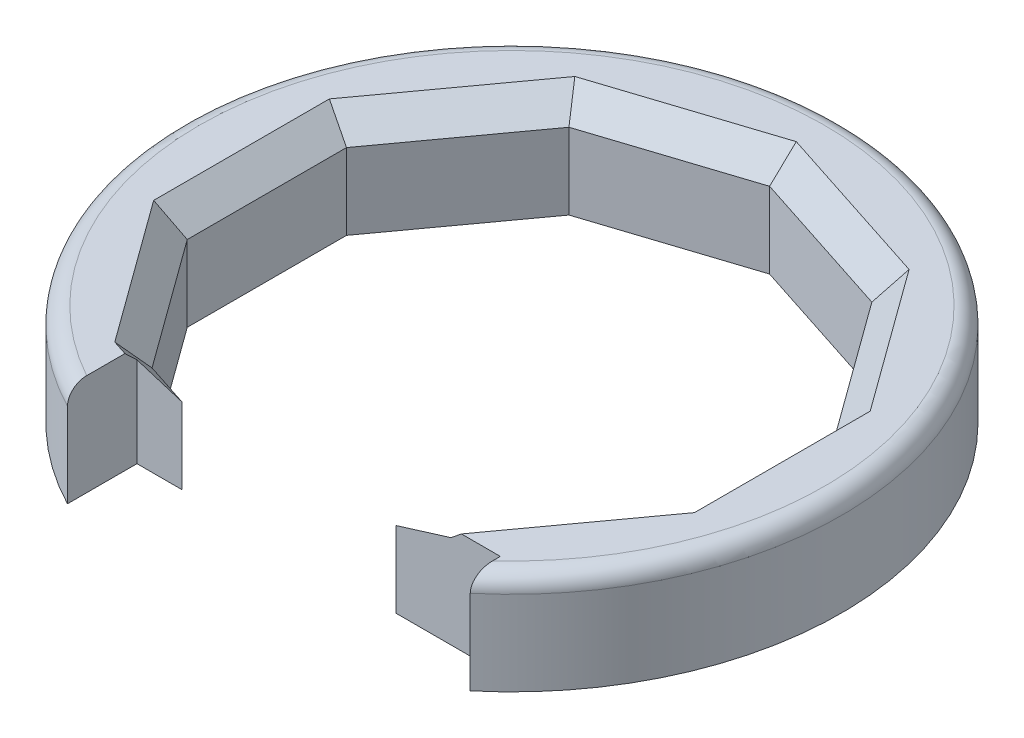
SolidWorks part; units mm, degrees
ref_plane "Front Plane" through (0, 0, 0) normal (0, 0, 1) x (1, 0, 0)
ref_plane "Top Plane" through (0, 0, 0) normal (0, 1, 0) x (1, 0, 0)
ref_plane "Right Plane" through (0, 0, 0) normal (1, 0, 0) x (0, 0, -1)
sketch "Sketch1" plane through (0, 0, 0) normal (0, 1, 0) x (1, 0, 0)
  line L1 (17.923, 24.6689) -> (0, 30.4924)
  line L2 (0, 30.4924) -> (-17.923, 24.6689)
  line L3 (-17.923, 24.6689) -> (-29, 9.4227)
  line L4 (-29, 9.4227) -> (-29, -9.4227)
  line L5 (-29, -9.4227) -> (-17.923, -24.6689)
  line L6 (-17.923, -24.6689) -> (0, -30.4924)
  line L7 (0, -30.4924) -> (17.923, -24.6689)
  line L8 (17.923, -24.6689) -> (29, -9.4227)
  line L9 (29, -9.4227) -> (29, 9.4227)
  line L10 (29, 9.4227) -> (17.923, 24.6689)
  circle A0 centre (0, 0) radius 39
  circle A1 centre (0, 0) radius 29 construction
  dimension "D1" = 78
  dimension "D2" = 10
extrude "Boss-Extrude1" add sketch "Sketch1" along normal blind 12
fillet "Fillet1" radius 2 1 edges at (0, 12, 39)
chamfer "Chamfer1" distance 3 angle 45 10 edges at (-8.9615, 12, 27.5806) (8.9615, 12, 27.5806) (23.4615, 12, 17.0458) (29, 12, 0) (23.4615, 12, -17.0458) (8.9615, 12, -27.5806) (-8.9615, 12, -27.5806) (-23.4615, 12, -17.0458) (-29, 12, 0) (-23.4615, 12, 17.0458)
sketch "Sketch2" plane through (0, 0, 0) normal (0, 1, 0) x (1, 0, 0)
  line L0 (0, 0) -> (0, -69.3722) construction
  line L1 (25, -69.3722) -> (-18, -69.3722)
  line L2 (25, -69.3722) -> (25, -26.3722)
  line L3 (25, -26.3722) -> (-18, -26.3722)
  line L4 (-18, -69.3722) -> (-18, -26.3722)
  line L5 (25, -69.3722) -> (-18, -26.3722) construction
  line L6 (25, -26.3722) -> (-18, -69.3722) construction
  line L7 (0, 0) -> (3.5, -47.8722) construction
  point P0 (3.5, -47.8722)
  point P8 (12.4285, -46.363)
  dimension "D1" = 7
  dimension "D2" = 48
  dimension "D3" = 43
  dimension "D4" = 43
extrude "Cut-Extrude2" cut sketch "Sketch2" along normal through all
